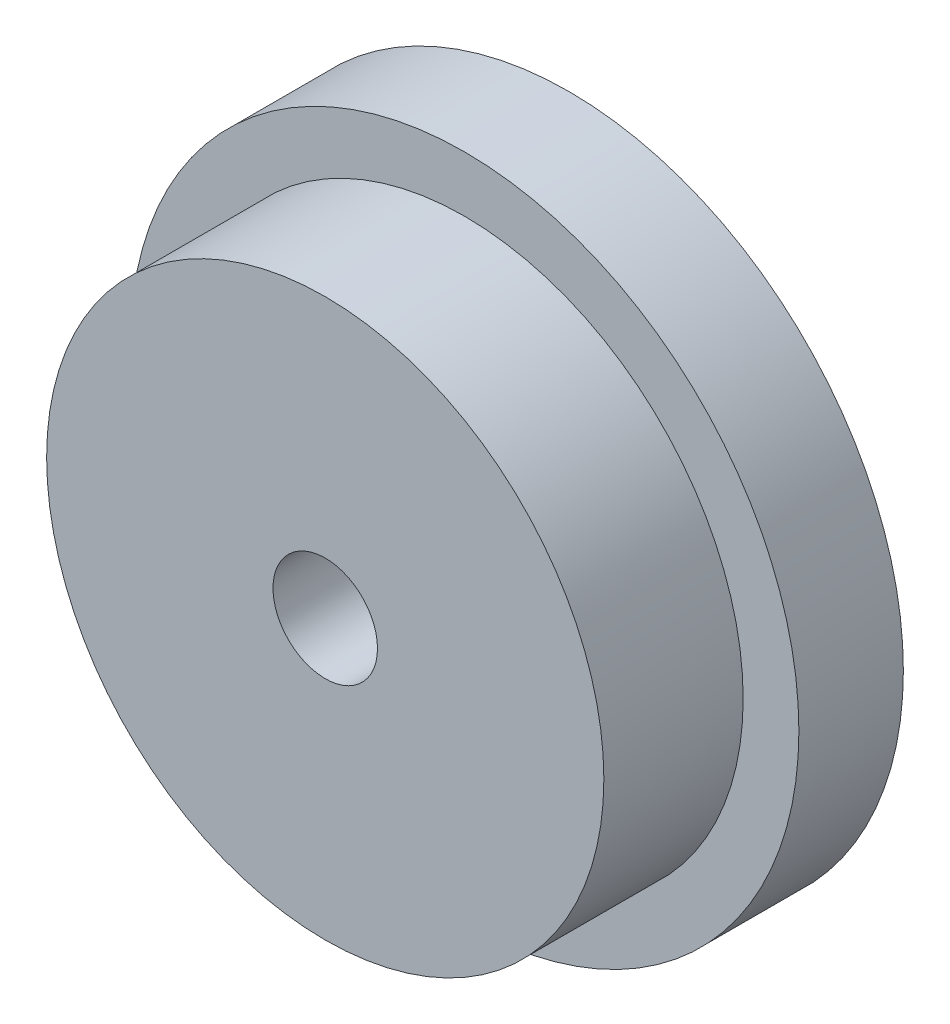
SolidWorks part; units mm, degrees
ref_plane "Front Plane" through (0, 0, 0) normal (0, 0, 1) x (1, 0, 0)
ref_plane "Top Plane" through (0, 0, 0) normal (0, 1, 0) x (1, 0, 0)
ref_plane "Right Plane" through (0, 0, 0) normal (1, 0, 0) x (0, 0, -1)
sketch "Sketch1" plane through (0, 0, 0) normal (0, 0, 1) x (1, 0, 0)
  circle A0 centre (0, 0) radius 30.48
  dimension "D1" = 60.96
extrude "Boss-Extrude1" add sketch "Sketch1" along normal blind 9.525
sketch "Sketch2" plane through (0, 0, 9.525) normal (0, 0, 1) x (1, 0, 0)
  circle A0 centre (0, 0) radius 25.4
  dimension "D1" = 50.8
extrude "Boss-Extrude2" add sketch "Sketch2" along normal blind 12.7
sketch "Sketch3" plane through (0, 0, 22.225) normal (0, 0, 1) x (1, 0, 0)
  circle A0 centre (0, 0) radius 4.7625
  dimension "D1" = 9.525
extrude "Cut-Extrude1" cut sketch "Sketch3" against normal through all
